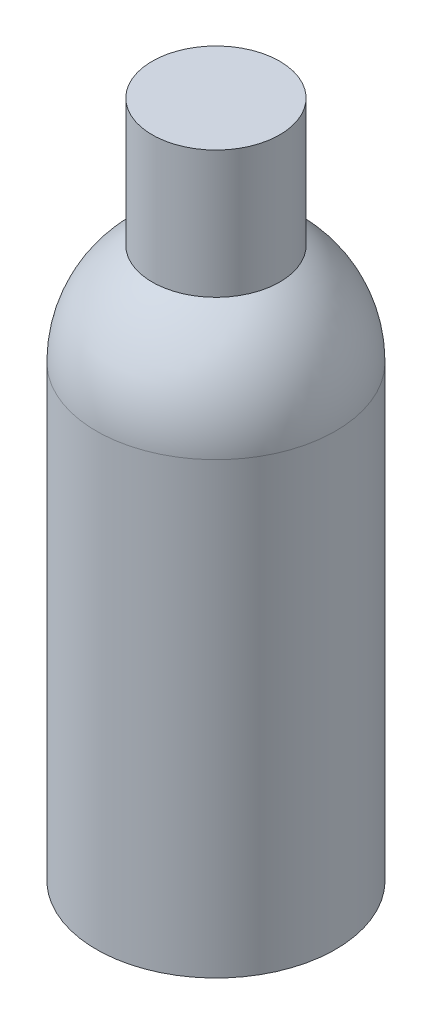
SolidWorks part; units mm, degrees
ref_plane "Přední rovina" through (0, 0, 0) normal (0, 0, 1) x (1, 0, 0)
ref_plane "Horní rovina" through (0, 0, 0) normal (0, 1, 0) x (1, 0, 0)
ref_plane "Pravá rovina" through (0, 0, 0) normal (1, 0, 0) x (0, 0, -1)
sketch "Skica1" plane through (0, 0, 0) normal (0, 0, 1) x (1, 0, 0)
  line L0 (0, 0) -> (0, 168.9343) construction
  line L1 (0, 0) -> (45, 0)
  line L2 (45, 0) -> (45, 168.9343)
  line L3 (24, 207) -> (24, 255)
  line L4 (24, 255) -> (0, 255)
  line L5 (0, 168.9343) -> (0, 255) construction
  line L6 (0, 0) -> (0, 255)
  arc A0 (45, 168.9343) -> (24, 207) centre (0, 168.9343) ccw
  point P7 (0, 0)
  dimension "D1" = 255
  dimension "D2" = 90
  dimension "D3" = 48
  dimension "D4" = 48
revolve "Rotovat1" add sketch "Skica1" angle 360 about L6
